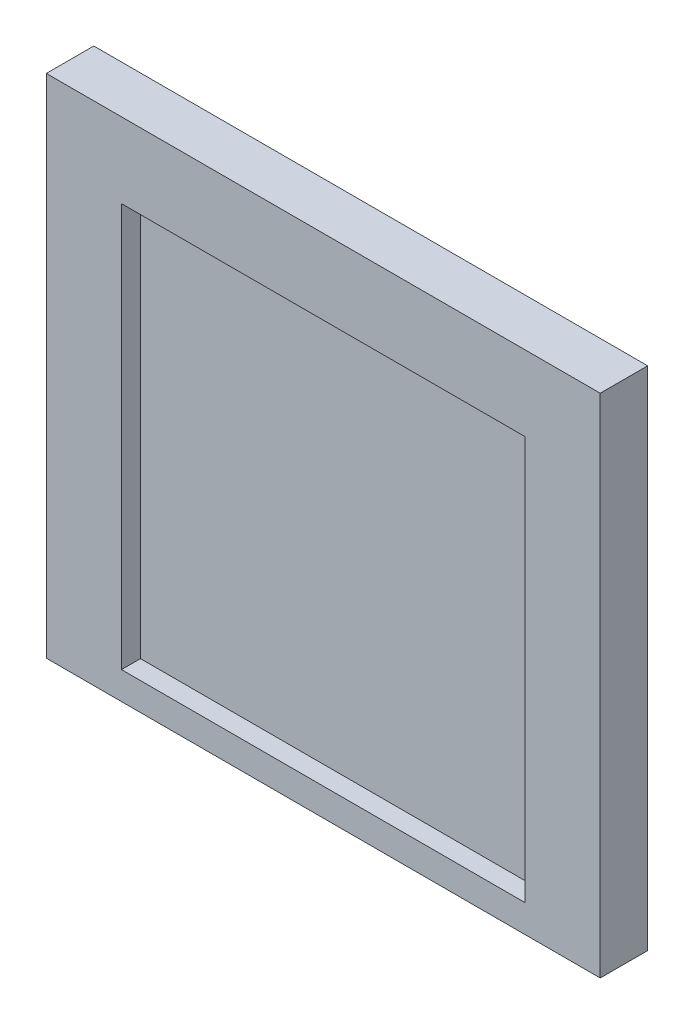
SolidWorks part; units mm, degrees
ref_plane "Front Plane" through (0, 0, 0) normal (0, 0, 1) x (1, 0, 0)
ref_plane "Top Plane" through (0, 0, 0) normal (0, 1, 0) x (1, 0, 0)
ref_plane "Right Plane" through (0, 0, 0) normal (1, 0, 0) x (0, 0, -1)
sketch "Sketch1" plane through (0, 0, 0) normal (0, 0, 1) x (1, 0, 0)
  line L1 (0, 0) -> (35, 0)
  line L2 (0, 0) -> (0, 35)
  line L3 (0, 35) -> (35, 35)
  line L4 (35, 0) -> (35, 35)
  dimension "D1" = 35
  dimension "D2" = 35
extrude "Boss-Extrude1" add sketch "Sketch1" along normal blind 3
sketch "Sketch2" plane through (0, 0, 3) normal (0, 0, 1) x (1, 0, 0)
  line L0 (17.5, 30.25) -> (17.5, 17.5) construction
  line L1 (4.75, 30.25) -> (30.25, 30.25)
  line L2 (4.75, 30.25) -> (4.75, 4.75)
  line L3 (4.75, 4.75) -> (30.25, 4.75)
  line L4 (30.25, 30.25) -> (30.25, 4.75)
  line L5 (17.5, 17.5) -> (4.75, 17.5) construction
  line L8 (17.5, 35) -> (17.5, 17.5) construction
  line L9 (35, 35) -> (0, 35) construction
  line L10 (17.5, 17.5) -> (35, 17.5) construction
  line L11 (35, 0) -> (35, 35) construction
  dimension "D1" = 25.5
  dimension "D2" = 25.5
extrude "Cut-Extrude1" cut sketch "Sketch2" against normal blind 1.2
sketch "Sketch3" plane through (0, 0, 0) normal (0, -1, 0) x (1, 0, 0)
  line L4 (0, 0) -> (35, 0)
  line L5 (35, 0) -> (35, 3)
  line L6 (35, 3) -> (0, 3)
  line L7 (0, 3) -> (0, 0)
  line L8 (0, 0) -> (35, 0)
  line L9 (35, 0) -> (35, 3)
  line L10 (35, 3) -> (0, 3)
  line L11 (0, 3) -> (0, 0)
  dimension "D1" = 0
extrude "Cut-Extrude2" cut sketch "Sketch3" against normal blind 3
